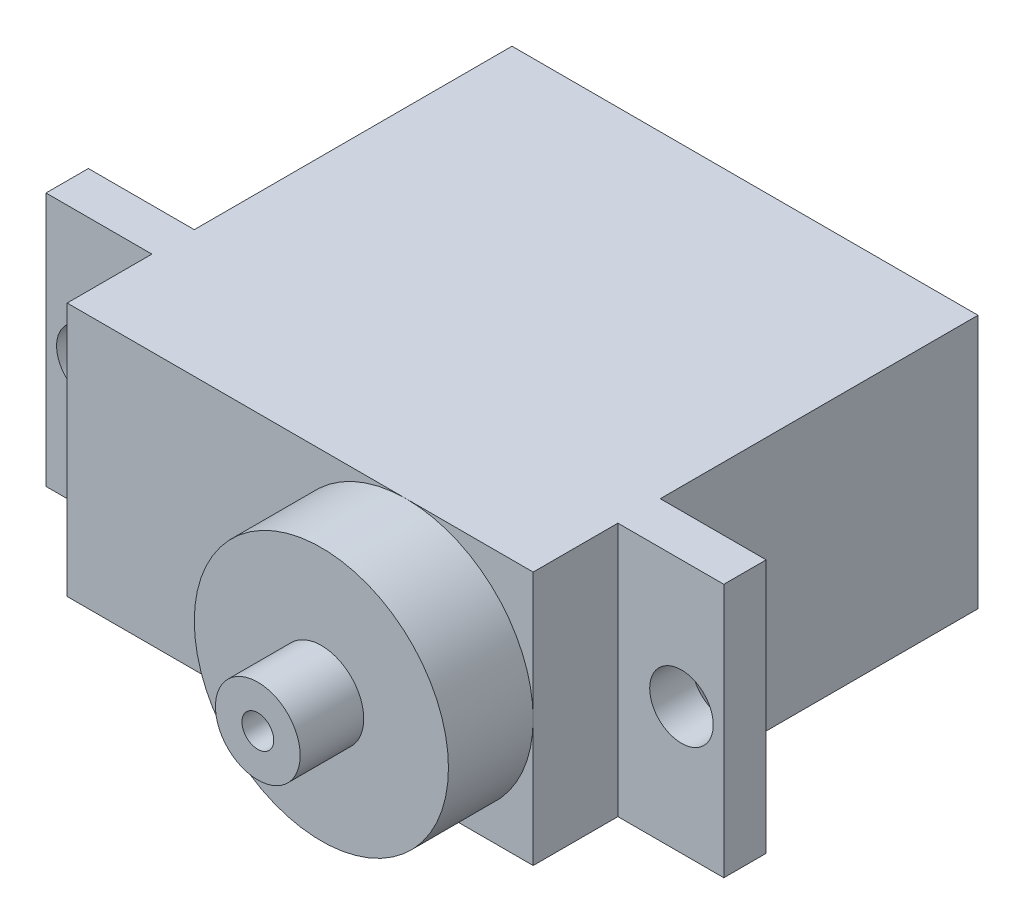
SolidWorks part; units mm, degrees
material "PET"
ref_plane "Alzado" through (0, 0, 0) normal (0, 0, 1) x (1, 0, 0)
ref_plane "Planta" through (0, 0, 0) normal (0, 1, 0) x (1, 0, 0)
ref_plane "Vista lateral" through (0, 0, 0) normal (1, 0, 0) x (0, 0, -1)
sketch "Croquis1" plane through (0, 0, 0) normal (0, 0, 1) x (1, 0, 0)
  line L1 (-16, 6) -> (16, 6)
  line L2 (-16, 6) -> (-16, -6)
  line L3 (-16, -6) -> (16, -6)
  line L4 (16, 6) -> (16, -6)
  line L5 (-16, 6) -> (16, -6) construction
  line L6 (-16, -6) -> (16, 6) construction
  point P0 (0, 0)
  dimension "D1" = 12
  dimension "D2" = 32
extrude "Saliente-Extruir1" add sketch "Croquis1" along normal blind 30
sketch "Croquis2" plane through (0, 0, 0) normal (0, 0, -1) x (-1, 0, 0)
  line L0 (16, -6) -> (-16, -6) construction
  line L1 (-16, 6) -> (-11, 6)
  line L2 (-16, 6) -> (-16, -6)
  line L3 (-16, -6) -> (-11, -6)
  line L4 (-11, 6) -> (-11, -6)
  line L6 (16, 6) -> (11, 6)
  line L7 (16, 6) -> (16, -6)
  line L8 (16, -6) -> (11, -6)
  line L9 (11, 6) -> (11, -6)
  dimension "D1" = 5
  dimension "D2" = 5
extrude "Cortar-Extruir1" cut sketch "Croquis2" against normal blind 15
sketch "Croquis3" plane through (0, 0, 30) normal (0, 0, 1) x (1, 0, 0)
  line L1 (-16, 6) -> (16, 6)
  line L2 (-16, 6) -> (-16, -6)
  line L3 (-16, -6) -> (16, -6)
  line L4 (16, 6) -> (16, -6)
extrude "Cortar-Extruir3" cut sketch "Croquis3" against normal blind 13
sketch "Croquis4" plane through (0, 0, 17) normal (0, 0, 1) x (1, 0, 0)
  line L0 (16, 6) -> (-16, 6) construction
  line L1 (-11, 6) -> (11, 6)
  line L2 (-11, 6) -> (-11, -6)
  line L3 (-11, -6) -> (11, -6)
  line L4 (11, 6) -> (11, -6)
  line L5 (-16, -6) -> (16, -6) construction
  dimension "D1" = 5
  dimension "D2" = 5
extrude "Saliente-Extruir2" add sketch "Croquis4" along normal blind 4
sketch "Croquis5" plane through (0, 0, 21) normal (0, 0, 1) x (1, 0, 0)
  line L0 (11, -6) -> (11, 6) construction
  circle A0 centre (5, 0) radius 6
  point P4 (11, 0)
  dimension "D1" = 6
extrude "Saliente-Extruir3" add sketch "Croquis5" along normal blind 4
sketch "Croquis6" plane through (0, 0, 25) normal (0, 0, 1) x (1, 0, 0)
  circle A0 centre (5, 0) radius 2
  dimension "D1" = 4
extrude "Saliente-Extruir4" add sketch "Croquis6" along normal blind 3
sketch "Croquis7" plane through (0, 0, 28) normal (0, 0, 1) x (1, 0, 0)
  circle A0 centre (5, 0) radius 0.75
  dimension "D1" = 1.5
extrude "Cortar-Extruir4" cut sketch "Croquis7" against normal blind 4
sketch "Croquis8" plane through (0, 0, 17) normal (0, 0, 1) x (1, 0, 0)
  line L0 (-11, 6) -> (-11, -6) construction
  circle A0 centre (-14, 0) radius 1.5
  point P4 (-11, 0)
  dimension "D1" = 3
  dimension "D2" = 3
extrude "Cortar-Extruir5" cut sketch "Croquis8" against normal blind 4
mirror "Simetría1" about plane through (0, 0, 0) normal (1, 0, 0) of "Cortar-Extruir5"
